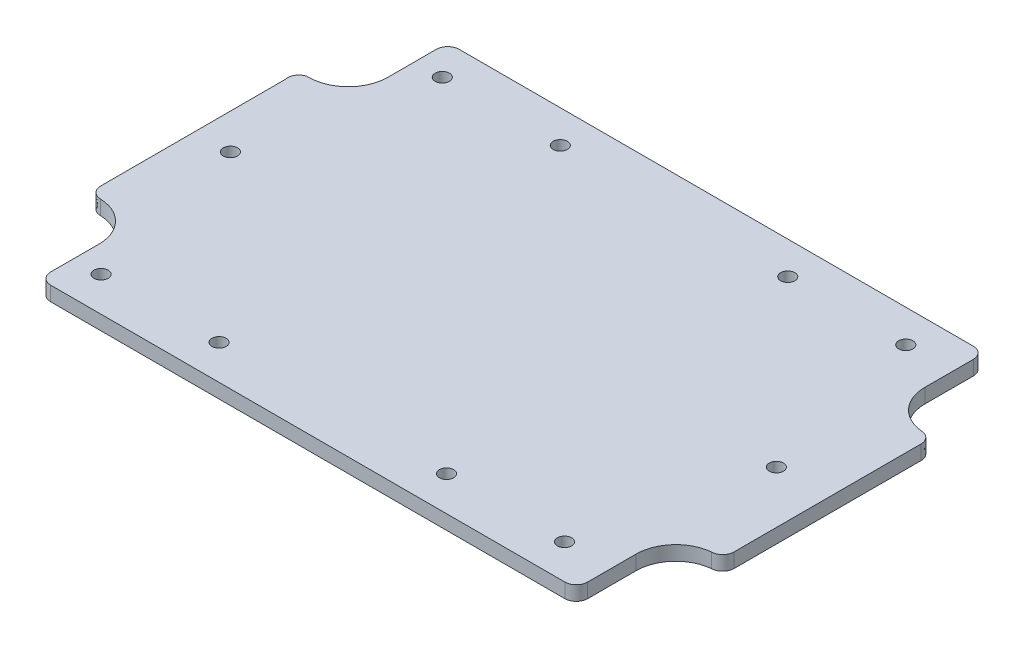
SolidWorks part; units mm, degrees
ref_plane "Front Plane" through (0, 0, 0) normal (0, 0, 1) x (1, 0, 0)
ref_plane "Top Plane" through (0, 0, 0) normal (0, 1, 0) x (1, 0, 0)
ref_plane "Right Plane" through (0, 0, 0) normal (1, 0, 0) x (0, 0, -1)
sketch "Sketch1" plane through (0, -3.8047, 0) normal (0, 1, 0) x (1, 0, 0)
  line L24 (49.5314, 40.4322) -> (49.5314, 48.9322)
  line L25 (47.517, 50.9466) -> (-42.883, 50.9466)
  line L26 (-44.8974, 48.9322) -> (-44.8974, 40.4322)
  line L27 (-53.5974, 31.0329) -> (-53.5974, -1.3729)
  line L28 (-44.8974, -10.3678) -> (-44.8974, -18.8678)
  line L29 (-42.883, -20.8822) -> (47.517, -20.8822)
  line L30 (49.5314, -18.8678) -> (49.5314, -10.3678)
  line L31 (57.8146, -1.3993) -> (57.8146, 31.4637)
  arc A0 (20.6296, 46.4594) -> (20.6296, 43.9594) centre (20.6296, 45.2094) ccw construction
  arc A1 (20.6296, 43.9594) -> (20.6296, 46.4594) centre (20.6296, 45.2094) ccw construction
  arc A2 (41.3796, 46.4594) -> (41.3796, 43.9594) centre (41.3796, 45.2094) ccw construction
  arc A3 (41.3796, 43.9594) -> (41.3796, 46.4594) centre (41.3796, 45.2094) ccw construction
  arc A4 (48.6296, 13.9594) -> (48.6296, 16.4594) centre (48.6296, 15.2094) ccw construction
  arc A5 (48.6296, 16.4594) -> (48.6296, 13.9594) centre (48.6296, 15.2094) ccw construction
  arc A6 (41.3796, -16.0406) -> (41.3796, -13.5406) centre (41.3796, -14.7906) ccw construction
  arc A7 (41.3796, -13.5406) -> (41.3796, -16.0406) centre (41.3796, -14.7906) ccw construction
  arc A8 (20.6296, -16.0406) -> (20.6296, -13.5406) centre (20.6296, -14.7906) ccw construction
  arc A9 (20.6296, -13.5406) -> (20.6296, -16.0406) centre (20.6296, -14.7906) ccw construction
  arc A10 (-19.3704, -16.0406) -> (-19.3704, -13.5406) centre (-19.3704, -14.7906) ccw construction
  arc A11 (-19.3704, -13.5406) -> (-19.3704, -16.0406) centre (-19.3704, -14.7906) ccw construction
  arc A12 (-40.1204, -13.5406) -> (-40.1204, -16.0406) centre (-40.1204, -14.7906) ccw construction
  arc A13 (-40.1204, -16.0406) -> (-40.1204, -13.5406) centre (-40.1204, -14.7906) ccw construction
  arc A14 (-47.3704, 16.4594) -> (-47.3704, 13.9594) centre (-47.3704, 15.2094) ccw construction
  arc A15 (-47.3704, 13.9594) -> (-47.3704, 16.4594) centre (-47.3704, 15.2094) ccw construction
  arc A16 (-40.1204, 46.4594) -> (-40.1204, 43.9594) centre (-40.1204, 45.2094) ccw construction
  arc A17 (-40.1204, 43.9594) -> (-40.1204, 46.4594) centre (-40.1204, 45.2094) ccw construction
  arc A18 (-19.3704, 46.4594) -> (-19.3704, 43.9594) centre (-19.3704, 45.2094) ccw construction
  arc A19 (-19.3704, 43.9594) -> (-19.3704, 46.4594) centre (-19.3704, 45.2094) ccw construction
  arc A20 (20.6296, 46.4594) -> (20.6296, 43.9594) centre (20.6296, 45.2094) ccw
  arc A21 (20.6296, 43.9594) -> (20.6296, 46.4594) centre (20.6296, 45.2094) ccw
  arc A22 (41.3796, 46.4594) -> (41.3796, 43.9594) centre (41.3796, 45.2094) ccw
  arc A23 (41.3796, 43.9594) -> (41.3796, 46.4594) centre (41.3796, 45.2094) ccw
  arc A24 (48.6296, 13.9594) -> (48.6296, 16.4594) centre (48.6296, 15.2094) ccw
  arc A25 (48.6296, 16.4594) -> (48.6296, 13.9594) centre (48.6296, 15.2094) ccw
  arc A26 (41.3796, -16.0406) -> (41.3796, -13.5406) centre (41.3796, -14.7906) ccw
  arc A27 (41.3796, -13.5406) -> (41.3796, -16.0406) centre (41.3796, -14.7906) ccw
  arc A28 (20.6296, -16.0406) -> (20.6296, -13.5406) centre (20.6296, -14.7906) ccw
  arc A29 (20.6296, -13.5406) -> (20.6296, -16.0406) centre (20.6296, -14.7906) ccw
  arc A30 (-19.3704, -16.0406) -> (-19.3704, -13.5406) centre (-19.3704, -14.7906) ccw
  arc A31 (-19.3704, -13.5406) -> (-19.3704, -16.0406) centre (-19.3704, -14.7906) ccw
  arc A32 (-40.1204, -13.5406) -> (-40.1204, -16.0406) centre (-40.1204, -14.7906) ccw
  arc A33 (-40.1204, -16.0406) -> (-40.1204, -13.5406) centre (-40.1204, -14.7906) ccw
  arc A34 (-47.3704, 16.4594) -> (-47.3704, 13.9594) centre (-47.3704, 15.2094) ccw
  arc A35 (-47.3704, 13.9594) -> (-47.3704, 16.4594) centre (-47.3704, 15.2094) ccw
  arc A36 (-40.1204, 46.4594) -> (-40.1204, 43.9594) centre (-40.1204, 45.2094) ccw
  arc A37 (-40.1204, 43.9594) -> (-40.1204, 46.4594) centre (-40.1204, 45.2094) ccw
  arc A38 (-19.3704, 46.4594) -> (-19.3704, 43.9594) centre (-19.3704, 45.2094) ccw
  arc A39 (-19.3704, 43.9594) -> (-19.3704, 46.4594) centre (-19.3704, 45.2094) ccw
  arc A58 (49.5314, 48.9322) -> (47.517, 50.9466) centre (47.517, 48.9322) ccw
  arc A59 (-42.883, 50.9466) -> (-44.8974, 48.9322) centre (-42.883, 48.9322) ccw
  arc A60 (-52.1883, 33.4533) -> (-44.8974, 40.4322) centre (-51.883, 40.4322) ccw
  arc A61 (-44.8974, -10.3678) -> (-51.6503, -3.386) centre (-51.883, -10.3678) ccw
  arc A62 (-44.8974, -18.8678) -> (-42.883, -20.8822) centre (-42.883, -18.8678) ccw
  arc A63 (47.517, -20.8822) -> (49.5314, -18.8678) centre (47.517, -18.8678) ccw
  arc A64 (55.8674, -3.4124) -> (49.5314, -10.3678) centre (56.517, -10.3678) ccw
  arc A65 (49.5314, 40.4322) -> (55.8674, 33.4769) centre (56.517, 40.4322) ccw
  arc A66 (20.6296, 45.4594) -> (20.6296, 44.9594) centre (20.6296, 45.2094) ccw
  arc A67 (20.6296, 44.9594) -> (20.6296, 45.4594) centre (20.6296, 45.2094) ccw
  arc A68 (41.3796, 45.4594) -> (41.3796, 44.9594) centre (41.3796, 45.2094) ccw
  arc A69 (41.3796, 44.9594) -> (41.3796, 45.4594) centre (41.3796, 45.2094) ccw
  arc A70 (48.6296, 14.9594) -> (48.6296, 15.4594) centre (48.6296, 15.2094) ccw
  arc A71 (48.6296, 15.4594) -> (48.6296, 14.9594) centre (48.6296, 15.2094) ccw
  arc A72 (41.3796, -15.0406) -> (41.3796, -14.5406) centre (41.3796, -14.7906) ccw
  arc A73 (41.3796, -14.5406) -> (41.3796, -15.0406) centre (41.3796, -14.7906) ccw
  arc A74 (20.6296, -15.0406) -> (20.6296, -14.5406) centre (20.6296, -14.7906) ccw
  arc A75 (20.6296, -14.5406) -> (20.6296, -15.0406) centre (20.6296, -14.7906) ccw
  arc A76 (-19.3704, -15.0406) -> (-19.3704, -14.5406) centre (-19.3704, -14.7906) ccw
  arc A77 (-19.3704, -14.5406) -> (-19.3704, -15.0406) centre (-19.3704, -14.7906) ccw
  arc A78 (-40.1204, -14.5406) -> (-40.1204, -15.0406) centre (-40.1204, -14.7906) ccw
  arc A79 (-40.1204, -15.0406) -> (-40.1204, -14.5406) centre (-40.1204, -14.7906) ccw
  arc A80 (-47.3704, 15.4594) -> (-47.3704, 14.9594) centre (-47.3704, 15.2094) ccw
  arc A81 (-47.3704, 14.9594) -> (-47.3704, 15.4594) centre (-47.3704, 15.2094) ccw
  arc A82 (-40.1204, 45.4594) -> (-40.1204, 44.9594) centre (-40.1204, 45.2094) ccw
  arc A83 (-40.1204, 44.9594) -> (-40.1204, 45.4594) centre (-40.1204, 45.2094) ccw
  arc A84 (-19.3704, 45.4594) -> (-19.3704, 44.9594) centre (-19.3704, 45.2094) ccw
  arc A85 (-19.3704, 44.9594) -> (-19.3704, 45.4594) centre (-19.3704, 45.2094) ccw
  spline S12 degree 3 poles (-52.1883, 33.4533) (-52.4357, 33.3836) (-52.9088, 33.1449) (-53.4256, 32.5527) (-53.6853, 31.8093) (-53.6588, 31.2819) (-53.5974, 31.0329) knots 0 0 0 0 0.001152 0.002305 0.003457 0.00461 0.00461 0.00461 0.00461
  spline S13 degree 3 poles (-53.5974, -1.3729) (-53.5974, -1.6299) (-53.4962, -2.15) (-53.0664, -2.8081) (-52.4214, -3.2599) (-51.9066, -3.3775) (-51.6503, -3.386) knots 0 0 0 0 0.001152 0.002305 0.003457 0.00461 0.00461 0.00461 0.00461
  spline S14 degree 3 poles (55.8674, -3.4124) (56.1243, -3.4039) (56.6408, -3.2853) (57.2842, -2.8339) (57.7142, -2.1742) (57.8146, -1.6557) (57.8146, -1.3993) knots 0 0 0 0 0.001152 0.002305 0.003457 0.00461 0.00461 0.00461 0.00461
  spline S15 degree 3 poles (57.8146, 31.4637) (57.8146, 31.7207) (57.7134, 32.2409) (57.2836, 32.899) (56.6386, 33.3508) (56.1238, 33.4684) (55.8674, 33.4769) knots 0 0 0 0 0.001152 0.002305 0.003457 0.00461 0.00461 0.00461 0.00461
  dimension "D2" = 1
extrude "Boss-Extrude2" add sketch "Sketch1" along normal blind 2.54 contours L31 S15 A65 L24 A58 L25 A59 L26 A60 S12 L27 S13 A61 L28 A62 L29 A63 L30 A64 S14 A21 A20 A23 A22 A25 A24 A27 A26 A29 A28 A31 A30 A33 A32 A35 A34 A37 A36 A39 A38
